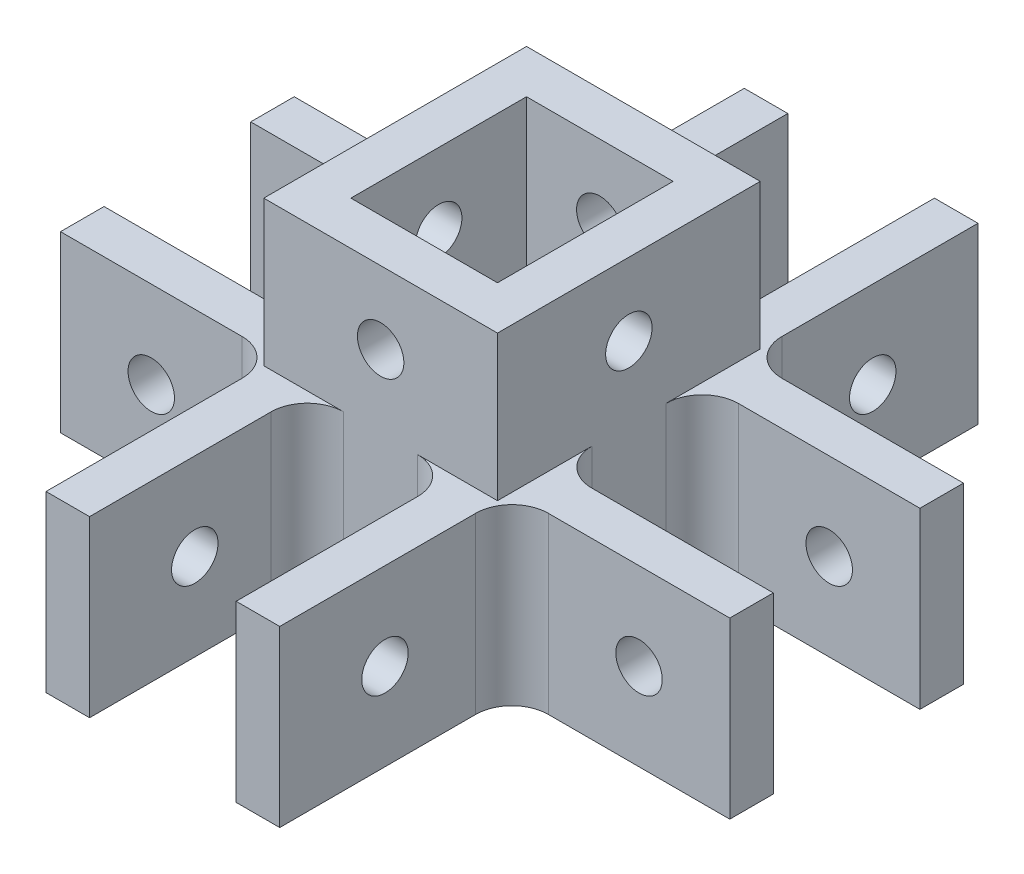
SolidWorks part; units mm, degrees
ref_plane "Plan de face" through (0, 0, 0) normal (0, 0, 1) x (1, 0, 0)
ref_plane "Plan de dessus" through (0, 0, 0) normal (0, 1, 0) x (1, 0, 0)
ref_plane "Plan de droite" through (0, 0, 0) normal (1, 0, 0) x (0, 0, -1)
sketch "Esquisse2" plane through (0, 0, 0) normal (0, 1, 0) x (1, 0, 0)
  line L0 (0, -6.05) -> (0, 6.05)
  line L1 (0, 6.05) -> (10.1, 6.05)
  line L2 (0, 11.55) -> (0, 24.05)
  line L3 (0, 24.05) -> (-3, 24.05)
  line L4 (-3, 24.05) -> (-3, 10.55)
  line L5 (-5.5, 8.05) -> (-18, 8.05)
  line L6 (-18, 8.05) -> (-18, 5.05)
  line L7 (-18, 5.05) -> (-5.5, 5.05)
  line L8 (2.5, 9.05) -> (7.6, 9.05)
  line L9 (-3, 2.55) -> (-3, -2.55)
  line L10 (0, 0) -> (-3, 0) construction
  line L11 (5.05, 9.05) -> (5.05, 6.05) construction
  line L12 (2.5, -9.05) -> (7.6, -9.05)
  line L13 (-18, -5.05) -> (-5.5, -5.05)
  line L14 (-18, -8.05) -> (-18, -5.05)
  line L15 (-5.5, -8.05) -> (-18, -8.05)
  line L16 (-3, -24.05) -> (-3, -10.55)
  line L17 (0, -24.05) -> (-3, -24.05)
  line L18 (0, -11.55) -> (0, -24.05)
  line L19 (0, -6.05) -> (10.1, -6.05)
  line L20 (10.1, 0) -> (13.1, 0) construction
  line L21 (10.1, -11.55) -> (10.1, -24.05)
  line L22 (10.1, -24.05) -> (13.1, -24.05)
  line L23 (13.1, -24.05) -> (13.1, -10.55)
  line L24 (15.6, -8.05) -> (28.1, -8.05)
  line L25 (28.1, -8.05) -> (28.1, -5.05)
  line L26 (28.1, -5.05) -> (15.6, -5.05)
  line L27 (13.1, 2.55) -> (13.1, -2.55)
  line L28 (28.1, 5.05) -> (15.6, 5.05)
  line L29 (28.1, 8.05) -> (28.1, 5.05)
  line L30 (15.6, 8.05) -> (28.1, 8.05)
  line L31 (13.1, 24.05) -> (13.1, 10.55)
  line L32 (10.1, 24.05) -> (13.1, 24.05)
  line L33 (10.1, 11.55) -> (10.1, 24.05)
  line L34 (10.1, -6.05) -> (10.1, 6.05)
  arc A0 (-5.5, 5.05) -> (-3, 2.55) centre (-5.5, 2.55) cw
  arc A1 (-3, 10.55) -> (-5.5, 8.05) centre (-5.5, 10.55) cw
  arc A2 (0, 11.55) -> (2.5, 9.05) centre (2.5, 11.55) ccw
  arc A3 (0, -11.55) -> (2.5, -9.05) centre (2.5, -11.55) cw
  arc A4 (-3, -10.55) -> (-5.5, -8.05) centre (-5.5, -10.55) ccw
  arc A5 (-5.5, -5.05) -> (-3, -2.55) centre (-5.5, -2.55) ccw
  arc A6 (15.6, -5.05) -> (13.1, -2.55) centre (15.6, -2.55) cw
  arc A7 (13.1, -10.55) -> (15.6, -8.05) centre (15.6, -10.55) cw
  arc A8 (10.1, -11.55) -> (7.6, -9.05) centre (7.6, -11.55) ccw
  arc A9 (10.1, 11.55) -> (7.6, 9.05) centre (7.6, 11.55) cw
  arc A10 (13.1, 10.55) -> (15.6, 8.05) centre (15.6, 10.55) ccw
  arc A11 (15.6, 5.05) -> (13.1, 2.55) centre (15.6, 2.55) ccw
  point P15 (-3, 5.05)
  point P18 (-3, 8.05)
  point P21 (0, 9.05)
  point P38 (0, -9.05)
  point P39 (-3, -8.05)
  point P40 (-3, -5.05)
  point P62 (5.05, -6.05)
  point P66 (5.05, -9.05)
  point P71 (13.1, -5.05)
  point P72 (13.1, -8.05)
  point P73 (10.1, -9.05)
  point P74 (10.1, 9.05)
  point P75 (13.1, 8.05)
  point P76 (13.1, 5.05)
  dimension "D7" = 2.5
  dimension "D1" = 6.05
  dimension "D2" = 5.05
  dimension "D3" = 3
  dimension "D4" = 3
  dimension "D5" = 15
  dimension "D6" = 5.05
  dimension "D9" = 15
extrude "Boss.-Extru.1" add sketch "Esquisse2" along normal blind 12
sketch "Esquisse3" plane through (0, 0, 8.05) normal (0, 0, 1) x (1, 0, 0)
  line L0 (-18, 0) -> (-5.5, 0) construction
  line L3 (-11.75, 0) -> (-11.75, 6) construction
  line L4 (-18, 6) -> (-11.75, 6) construction
  line L5 (-18, 12) -> (-18, 0) construction
  circle A0 centre (-11.75, 6) radius 1.6
  dimension "D1" = 3.2
extrude "Enlèv. mat.-Extru.1" cut sketch "Esquisse3" against normal up to surface (16.1 mm away) up to face at (-11.75, 6, -8.05)
ref_plane "Plan1" through (5.05, 0, 0) normal (1, 0, 0) x (0, 0, -1)
mirror "Symétrie1" about plane through (5.05, 0, 0) normal (1, 0, 0) of "Enlèv. mat.-Extru.1"
ref_plane "Plan2" through (2.525, 0, -2.525) normal (-0.7071, 0, 0.7071) x (0.7071, 0, 0.7071)
mirror "Symétrie6" about plane through (2.525, 0, -2.525) normal (-0.7071, 0, 0.7071) of "Symétrie1", "Enlèv. mat.-Extru.1"
sketch "Esquisse4" plane through (0, 12, 0) normal (0, 1, 0) x (1, 0, 0)
  line L0 (7.6, 9.05) -> (2.5, 9.05) construction
  line L1 (2.5, -9.05) -> (7.6, -9.05) construction
  line L3 (-3, 9.05) -> (13.1, 9.05)
  line L6 (-3, 9.05) -> (-3, -9.05)
  line L8 (-3, -9.05) -> (13.1, -9.05)
  line L11 (13.1, 9.05) -> (13.1, -9.05)
  line L14 (13.1, -2.55) -> (13.1, 2.55) construction
  line L15 (-3, 2.55) -> (-3, -2.55) construction
extrude "Extru.-Mince1" add sketch "Esquisse4" along normal blind 10 thin
sketch "Esquisse5" plane through (0, 0, -9.05) normal (0, 0, -1) x (-1, 0, 0)
  line L0 (-5.05, 22) -> (-5.05, 17) construction
  line L1 (-13.1, 22) -> (3, 22) construction
  line L2 (-5.05, 17) -> (-13.1, 17) construction
  line L3 (-13.1, 22) -> (-13.1, 12) construction
  circle A0 centre (-5.05, 17) radius 1.6
  dimension "D1" = 3.2
extrude "Enlèv. mat.-Extru.2" cut sketch "Esquisse5" against normal through all
mirror "Symétrie10" about plane through (2.525, 0, -2.525) normal (-0.7071, 0, 0.7071) of "Enlèv. mat.-Extru.2"
